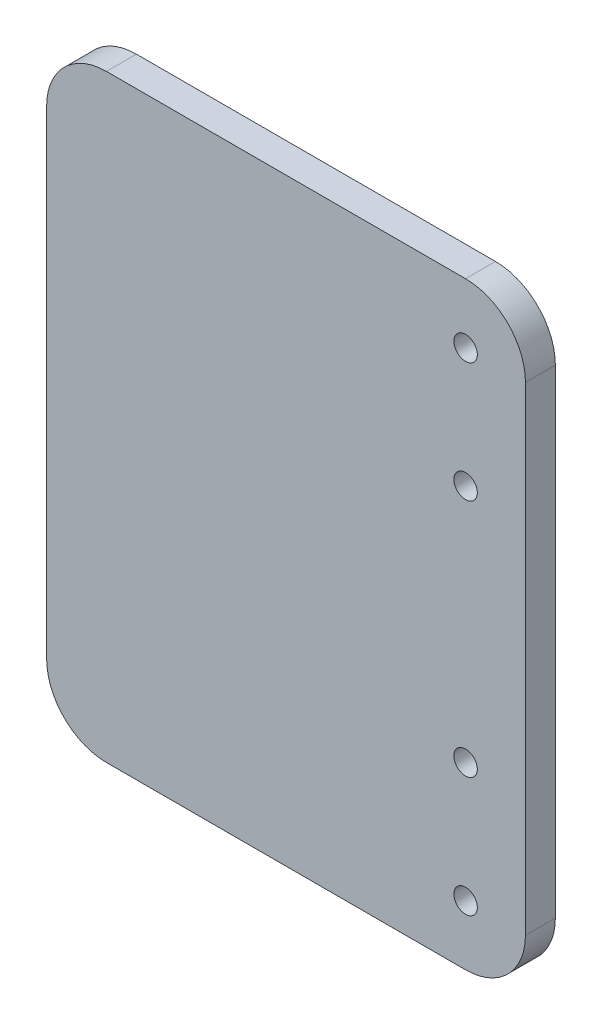
SolidWorks part; units mm, degrees
ref_plane "Front Plane" through (0, 0, 0) normal (1, 0, 0) x (0, 1, 0)
ref_plane "Top Plane" through (0, 0, 0) normal (0, 0, 1) x (0, 1, 0)
ref_plane "Right Plane" through (0, 0, 0) normal (0, 1, 0) x (-1, 0, 0)
sketch "Sketch1" plane through (0, 0, 0) normal (0, 0, 1) x (0, 1, 0)
  line L1 (-63.5, -50.8) -> (63.5, -50.8)
  line L2 (-63.5, -50.8) -> (-63.5, 50.8)
  line L3 (-63.5, 50.8) -> (63.5, 50.8)
  line L4 (63.5, -50.8) -> (63.5, 50.8)
  line L5 (-63.5, -50.8) -> (63.5, 50.8) construction
  line L6 (-63.5, 50.8) -> (63.5, -50.8) construction
  point P0 (0, 0)
  dimension "D1" = 127
  dimension "D2" = 101.6
extrude "Boss-Extrude1" add sketch "Sketch1" along normal blind 6.35
sketch "Sketch2" plane through (0, 0, 6.35) normal (0, 0, 1) x (1, 0, 0)
  line L0 (-50.8, -63.5) -> (50.8, -63.5) construction
  line L1 (50.8, -63.5) -> (50.8, 63.5) construction
  point P0 (38.1, -50.8)
  point P1 (38.1, -25.4)
  point P2 (38.1, 25.4)
  point P3 (38.1, 50.8)
  point P4 (0, 0)
  dimension "D1" = 25.4
  dimension "D2" = 25.4
  dimension "D3" = 12.7
  dimension "D4" = 50.8
  dimension "D5" = 12.7
hole_wizard "#9 (0.196) Diameter Hole1" positions "Sketch2" profile "Sketch3" hole size "#9" standard "ANSI Inch" end condition through all
sketch "Sketch3" plane through (38.1, -50.8, 6.35) normal (1, 0, 0) x (0, -1, 0)
  line L0 (0, 0) -> (0, 6.35)
  line L1 (0, 6.35) -> (2.4892, 6.35)
  line L2 (2.4892, 6.35) -> (2.4892, 0)
  line L5 (2.4892, 0) -> (0, 0)
  line L11 (0, -6.35) -> (0, 107.95) construction
  dimension "Thru Hole Dia." = 4.9784
  dimension "Thru Hole Depth" = 6.35
fillet "Fillet1" radius 12.7 4 edges at (-50.8, -63.5, 3.175) (50.8, -63.5, 3.175) (50.8, 63.5, 3.175) (-50.8, 63.5, 3.175)
